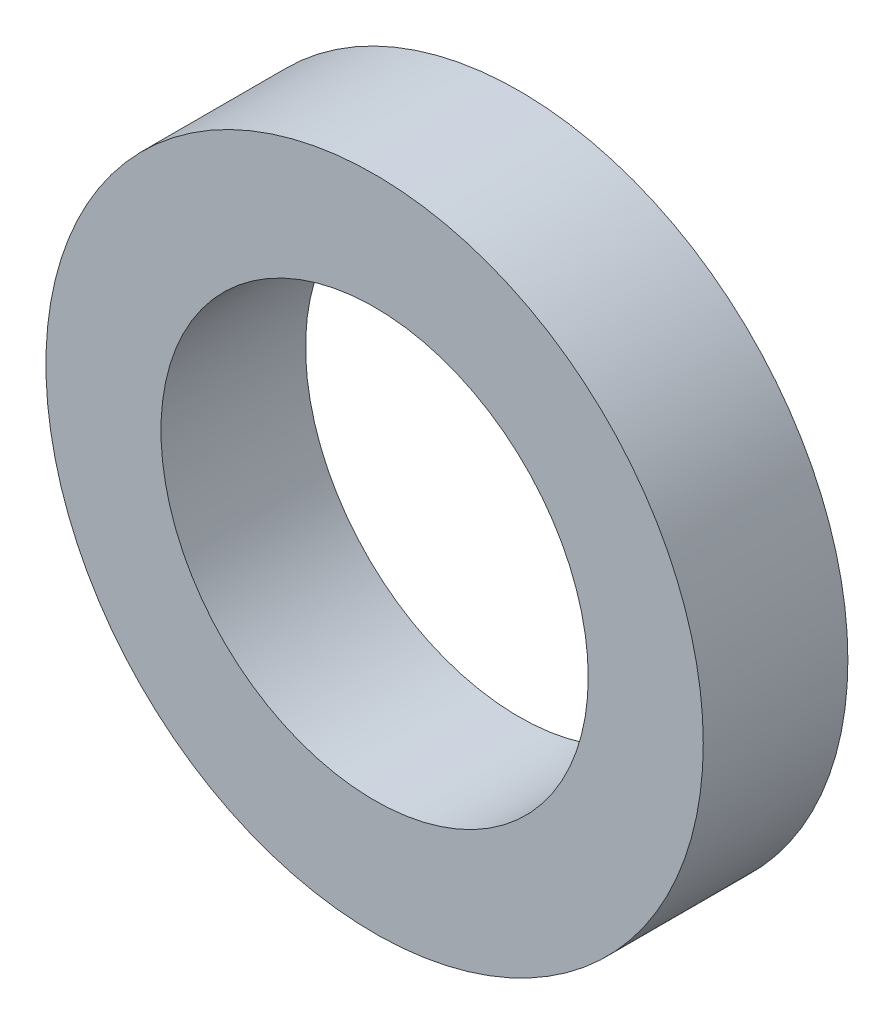
SolidWorks part; units mm, degrees
material "VITON"
ref_plane "Front Plane" through (0, 0, 0) normal (0, 0, 1) x (1, 0, 0)
ref_plane "Top Plane" through (0, 0, 0) normal (0, 1, 0) x (1, 0, 0)
ref_plane "Right Plane" through (0, 0, 0) normal (1, 0, 0) x (0, 0, -1)
sketch "Sketch1" plane through (0, 0, 0) normal (0, 0, 1) x (1, 0, 0)
  circle A0 centre (0, 0) radius 3.25
  circle A1 centre (0, 0) radius 5
  dimension "D1" = 6.5
  dimension "D2" = 10
extrude "Boss-Extrude1" add sketch "Sketch1" along normal blind 2.2
